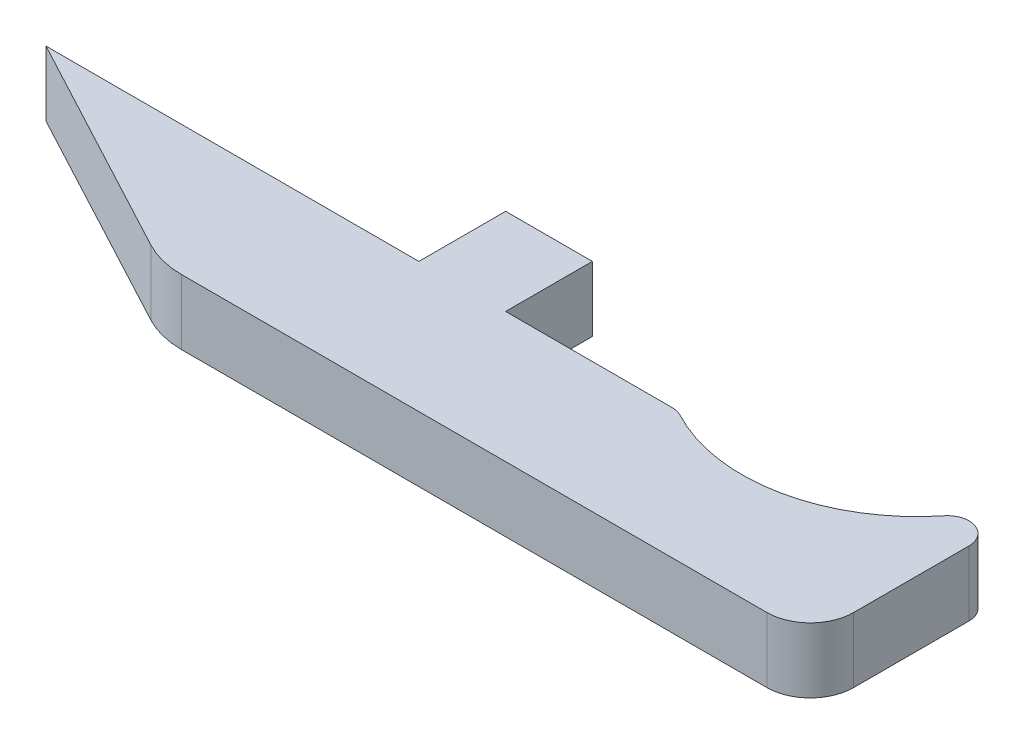
SolidWorks part; units mm, degrees
material "AISI 4130 Steel, annealed at 865C"
ref_plane "X-Y Datum" through (0, 0, 0) normal (0, 0, 1) x (1, 0, 0)
ref_plane "X-Z Datum" through (0, 0, 0) normal (0, 1, 0) x (1, 0, 0)
ref_plane "Y-Z Datum" through (0, 0, 0) normal (1, 0, 0) x (0, 0, -1)
sketch "Sketch1" plane through (0, 0, 0) normal (0, 1, 0) x (1, 0, 0)
  line L0 (58.9432, -34.753) -> (58.9432, -34.7341) construction
  line L1 (58.9432, -45.8687) -> (3.2156, -45.8687)
  line L2 (58.9432, -45.8687) -> (58.9432, -34.7435)
  line L3 (24.1452, -55.3937) -> (71.7702, -55.3937)
  line L4 (71.7702, -34.7435) -> (71.7702, -55.3937)
  line L5 (6.2845, -45.8687) -> (24.1452, -55.3937)
  line L8 (33.5895, -45.8687) -> (3.1095, -45.8687) construction
  line L9 (33.5895, -45.8687) -> (3.1095, -45.8687)
  circle A0 centre (58.9432, -34.7435) radius 12.827
  circle A1 centre (58.9432, -34.7435) radius 12.7
  circle A2 centre (58.9432, -34.7435) radius 12.7 construction
  dimension "D3" = 25.654
  dimension "D5" = 9.525
  dimension "D1" = 55.7276
  dimension "D2" = 11.1252
  dimension "D4" = 3.175
  dimension "D6" = 47.625
extrude "Boss-Extrude1" add sketch "Sketch1" along normal blind 4.7625
fillet "Fillet1" radius 1.5875 2 edges at (52.5587, 2.3813, 45.8687) (71.7702, 2.3813, 34.7435)
fillet "Fillet2" radius 6.35 1 edges at (24.1452, 2.3813, 55.3937)
fillet "Fillet3" radius 3.175 1 edges at (71.7702, 2.3813, 55.3937)
sketch "Sketch2" plane through (0, 0, 45.8687) normal (0, 0, -1) x (-1, 0, 0)
  line L0 (-52.1488, 4.7625) -> (-6.2845, 4.7625) construction
  line L1 (-39.9395, 4.7625) -> (-33.5895, 4.7625)
  line L2 (-39.9395, 4.7625) -> (-39.9395, 0)
  line L3 (-39.9395, 0) -> (-33.5895, 0)
  line L4 (-33.5895, 4.7625) -> (-33.5895, 0)
  line L5 (-52.1488, 0) -> (-6.2845, 0) construction
  line L6 (-6.2845, 4.7625) -> (-6.2845, 0) construction
  dimension "D1" = 27.305
  dimension "D2" = 6.35
extrude "Boss-Extrude2" add sketch "Sketch2" along normal blind 6.35
fillet "Fillet4" [suppressed] radius 0.7937
